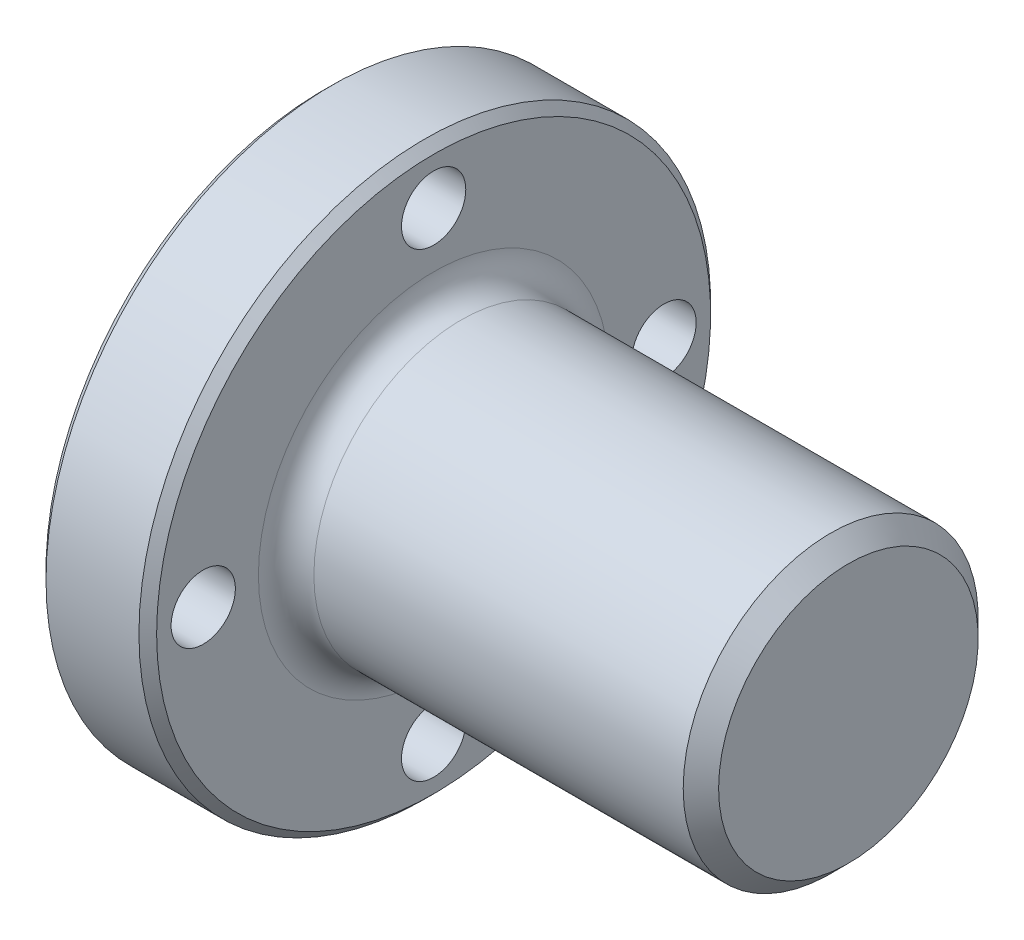
SolidWorks part; units mm, degrees
ref_plane "Front Plane" through (0, 0, 0) normal (0, 0, 1) x (1, 0, 0)
ref_plane "Top Plane" through (0, 0, 0) normal (0, 1, 0) x (1, 0, 0)
ref_plane "Right Plane" through (0, 0, 0) normal (1, 0, 0) x (0, 0, -1)
sketch "Sketch1" plane through (0, 0, 0) normal (0, 1, 0) x (1, 0, 0)
  line L0 (-25.0317, 0) -> (-25.0317, 8.7122)
  line L1 (-25.0317, 8.7122) -> (-20.2057, 8.7122)
  line L2 (-20.2057, 8.7122) -> (-20.2057, 24.6126)
  line L3 (-20.2057, 24.6126) -> (-10.6807, 24.6126)
  line L4 (-10.6807, 24.6126) -> (-10.6807, 12.7)
  line L5 (-10.6807, 12.7) -> (25.0317, 12.7)
  line L6 (25.0317, 12.7) -> (25.0317, 0)
  line L7 (25.0317, 0) -> (-25.0317, 0)
  line L8 (-50.4317, 0) -> (50.4317, 0) construction
  point P10 (0, 0)
  dimension "D1" = 35.7124
  dimension "D2" = 45.2374
  dimension "D3" = 50.0634
  dimension "D4" = 11.9126
  dimension "D5" = 15.9004
  dimension "D6" = 24.6126
revolve "Revolve1" add sketch "Sketch1" angle 360 about L8
fillet "Fillet1" radius 2.3876 1 edges at (-10.6807, 0, 12.7)
chamfer "Chamfer1" distance 0.762 angle 45 3 edges at (-10.6807, 0, 24.6126) (-20.2057, 0, 24.6126) (-25.0317, 0, 8.7122)
chamfer "Chamfer2" distance 1.524 angle 45 1 edges at (25.0317, 0, 12.7)
sketch "Sketch2" plane through (0, 0, 0) normal (1, 0, 0) x (0, 0, -1)
  circle A0 centre (19.8374, 0) radius 2.7686
  circle A1 centre (0, 19.8374) radius 2.7686
  circle A2 centre (-19.8374, 0) radius 2.7686
  circle A3 centre (0, -19.8374) radius 2.7686
  point P8 (0, 0)
  dimension "D1" = 5.5372
  dimension "D2" = 5.5372
  dimension "D3" = 5.5372
  dimension "D4" = 5.5372
  dimension "D5" = 19.8374
  dimension "D6" = 39.6748
  dimension "D7" = 19.8374
  dimension "D8" = 39.6748
extrude "Cut-Extrude2" cut sketch "Sketch2" against normal blind 10.6807 from offset 10.6807
